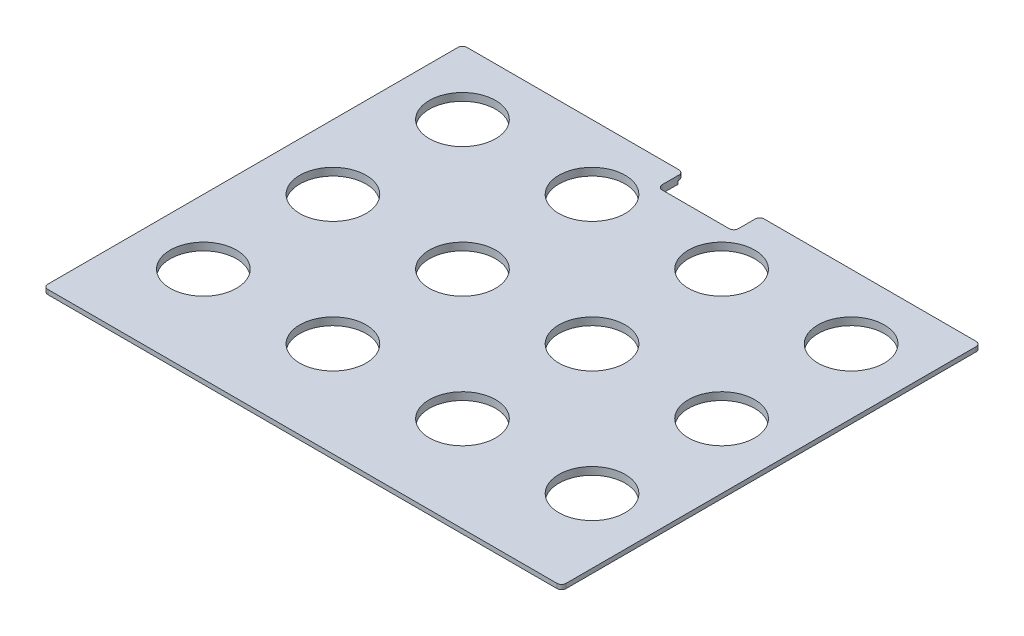
SolidWorks part; units mm, degrees
ref_plane "前基準面" through (0, 0, 0) normal (0, 0, 1) x (1, 0, 0)
ref_plane "上基準面" through (0, 0, 0) normal (0, 1, 0) x (1, 0, 0)
ref_plane "右基準面" through (0, 0, 0) normal (1, 0, 0) x (0, 0, -1)
sketch "草圖1" plane through (0, 0, 0) normal (0, 1, 0) x (1, 0, 0)
  line L1 (170, -127.5) -> (-170, -127.5)
  line L2 (170, -127.5) -> (170, 127.5)
  line L3 (170, 127.5) -> (-170, 127.5)
  line L4 (-170, -127.5) -> (-170, 127.5)
  line L5 (170, -127.5) -> (-170, 127.5) construction
  line L6 (170, 127.5) -> (-170, -127.5) construction
  point P0 (0, 0)
  dimension "D1" = 340
  dimension "D2" = 255
extrude "填料-伸長1" add sketch "草圖1" along normal blind 3
sketch "草圖2" plane through (0, 0, 0) normal (0, -1, 0) x (1, 0, 0)
  line L0 (-166.5, 100.5) -> (-143, 124)
  line L1 (166.5, -124) -> (-166.5, -124)
  line L2 (166.5, -124) -> (166.5, 124) construction
  line L3 (166.5, 124) -> (-166.5, 124) construction
  line L4 (-166.5, -124) -> (-166.5, 124) construction
  line L5 (166.5, -124) -> (-166.5, 124) construction
  line L6 (166.5, 124) -> (-166.5, -124) construction
  line L7 (143, 124) -> (166.5, 100.5)
  line L8 (-166.5, 100.5) -> (-166.5, -124)
  line L9 (-143, 124) -> (143, 124)
  line L10 (166.5, 100.5) -> (166.5, -124)
  point P0 (0, 0)
  dimension "D1" = 333
  dimension "D2" = 248
  dimension "D3" = 23.5
  dimension "D4" = 23.5
  dimension "D5" = 23.5
  dimension "D6" = 23.5
extrude "填料-伸長2" add sketch "草圖2" along normal blind 2
sketch "草圖3" plane through (0, 3, 0) normal (0, 1, 0) x (1, 0, 0)
  line L0 (170, 127.5) -> (-170, 127.5) construction
  line L2 (-170, -127.5) -> (170, -127.5) construction
  line L3 (0, -1.65) -> (0, 1.65) construction
  line L4 (-170, 127.5) -> (-170, -127.5) construction
  line L5 (-25, 127.5) -> (25, 127.5)
  line L6 (-25, 127.5) -> (-25, 110.5)
  line L7 (-25, 110.5) -> (25, 110.5)
  line L8 (25, 127.5) -> (25, 110.5)
  circle A0 centre (-127.5, 85) radius 21.75
  circle A1 centre (-42.5, 85) radius 21.75
  circle A2 centre (-127.5, 0) radius 21.75
  circle A3 centre (-42.5, 0) radius 21.75
  circle A4 centre (-127.5, -85) radius 21.75
  circle A5 centre (-42.5, -85) radius 21.75
  circle A6 centre (127.5, -85) radius 21.75
  circle A7 centre (42.5, -85) radius 21.75
  circle A8 centre (42.5, 0) radius 21.75
  circle A9 centre (127.5, 0) radius 21.75
  circle A10 centre (127.5, 85) radius 21.75
  circle A11 centre (42.5, 85) radius 21.75
  dimension "D1" = 43.5
  dimension "D2" = 42.5
  dimension "D4" = 43.5
  dimension "D5" = 43.5
  dimension "D6" = 43.5
  dimension "D9" = 43.5
  dimension "D10" = 43.5
  dimension "D14" = 17
  dimension "D3" = 85
  dimension "D7" = 85
  dimension "D8" = 85
  dimension "D11" = 85
  dimension "D12" = 42.5
  dimension "D13" = 42.5
  dimension "D16" = 50
  dimension "D17" = 25
extrude "除料-伸長1" cut sketch "草圖3" against normal blind 5
sketch "草圖4" plane through (0, 3, 0) normal (0, 1, 0) x (1, 0, 0)
  line L0 (170, -127.5) -> (170, 127.5) construction
  line L1 (-170, -127.5) -> (170, -127.5)
  line L2 (-170, -127.5) -> (-170, -147.5)
  line L3 (-170, -147.5) -> (170, -147.5)
  line L4 (170, -127.5) -> (170, -147.5)
  dimension "D1" = 20
extrude "填料-伸長3" add sketch "草圖4" against normal up to vertex
fillet "圓角1" radius 3 8 edges at (-170, 1.5, -127.5) (170, 1.5, -127.5) (170, 1.5, 147.5) (-170, 1.5, 147.5) (25, 0.5, -110.5) (25, 1.5, -127.5) (-25, 0.5, -110.5) (-25, 1.5, -127.5)
